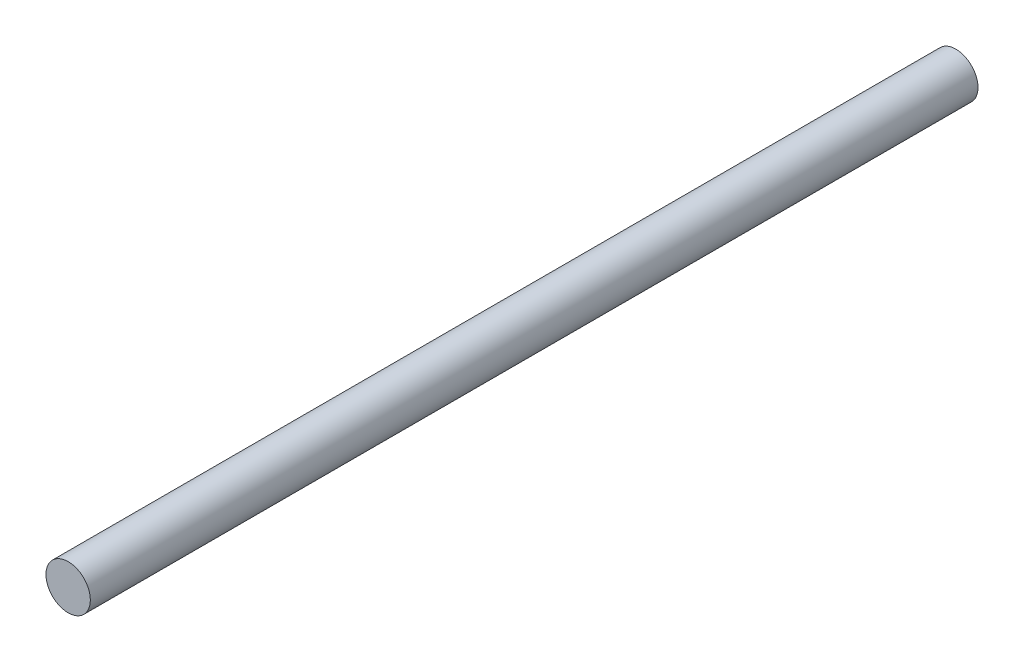
SolidWorks part; units mm, degrees
ref_plane "Front Plane" through (0, 0, 0) normal (0, 0, 1) x (1, 0, 0)
ref_plane "Top Plane" through (0, 0, 0) normal (0, 1, 0) x (1, 0, 0)
ref_plane "Right Plane" through (0, 0, 0) normal (1, 0, 0) x (0, 0, -1)
sketch "Sketch1" plane through (0, 0, 0) normal (0, 0, 1) x (1, 0, 0)
  circle A0 centre (0, 0) radius 3
  dimension "D1" = 6
extrude "Boss-Extrude1" add sketch "Sketch1" along normal blind 120
